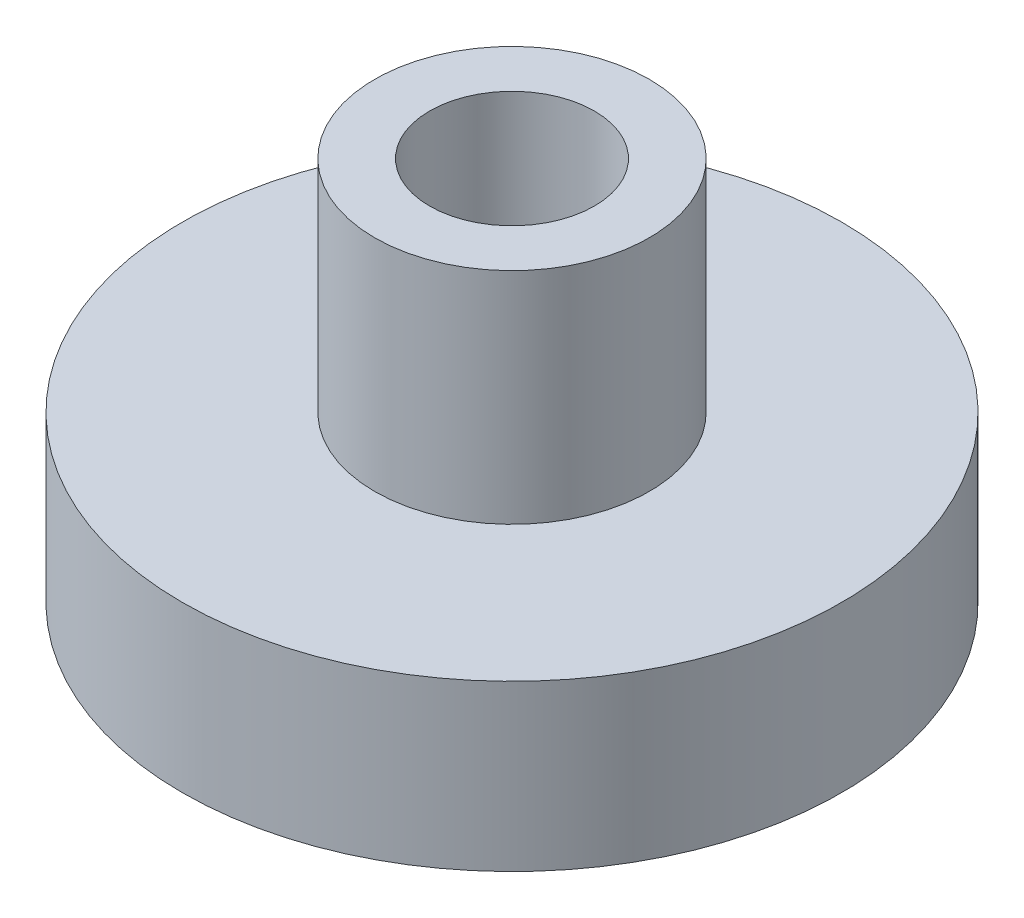
SolidWorks part; units mm, degrees
material "聚脂树脂"
ref_plane "前视基准面" through (0, 0, 0) normal (0, 0, 1) x (1, 0, 0)
ref_plane "上视基准面" through (0, 0, 0) normal (0, 1, 0) x (1, 0, 0)
ref_plane "右视基准面" through (0, 0, 0) normal (1, 0, 0) x (0, 0, -1)
other "Configuration Table"
sketch "草图1" plane through (0, 0, 0) normal (0, 1, 0) x (1, 0, 0)
  circle A0 centre (0, 0) radius 2.5
  circle A1 centre (0, 0) radius 1.5
  dimension "D1" = 3
  dimension "D2" = 5
extrude "凸台-拉伸1" add sketch "草图1" along normal blind 4
sketch "草图2" plane through (0, 0, 0) normal (0, -1, 0) x (1, 0, 0)
  circle A0 centre (0, 0) radius 1.5
  circle A1 centre (0, 0) radius 6
  dimension "D1" = 3
  dimension "D2" = 12
extrude "凸台-拉伸2" add sketch "草图2" along normal blind 3
